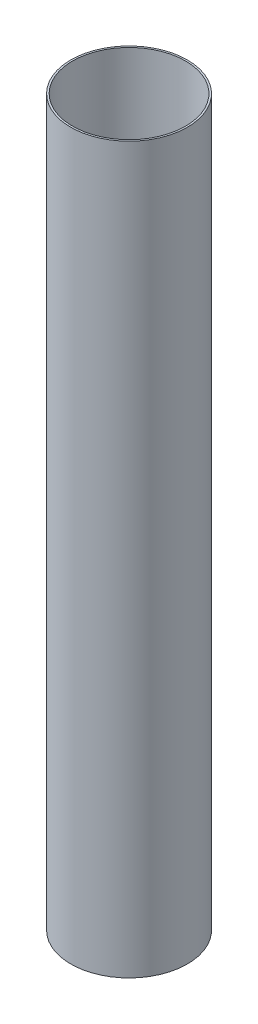
SolidWorks part; units mm, degrees
material "A-Glass Fiber"
ref_plane "Front Plane" through (0, 0, 0) normal (0, 0, 1) x (1, 0, 0)
ref_plane "Top Plane" through (0, 0, 0) normal (0, 1, 0) x (1, 0, 0)
ref_plane "Right Plane" through (0, 0, 0) normal (1, 0, 0) x (0, 0, -1)
sketch "Sketch1" plane through (0, 0, 0) normal (0, 1, 0) x (1, 0, 0)
  circle A0 centre (0, 0) radius 49.53
  circle A1 centre (0, 0) radius 51.1048
  dimension "D1" = 99.06
  dimension "D2" = 1.5748
extrude "Boss-Extrude1" add sketch "Sketch1" along normal blind 635
